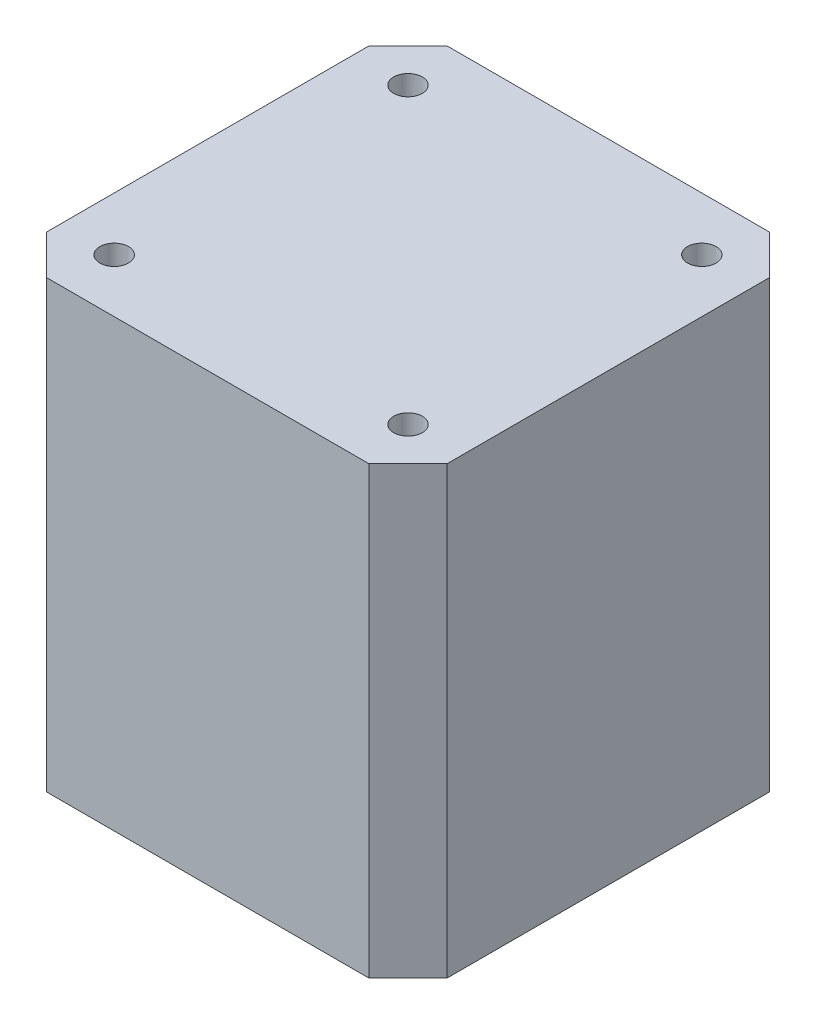
SolidWorks part; units mm, degrees
ref_plane "Front Plane" through (0, 0, 0) normal (0, 0, 1) x (1, 0, 0)
ref_plane "Top Plane" through (0, 0, 0) normal (0, 1, 0) x (1, 0, 0)
ref_plane "Right Plane" through (0, 0, 0) normal (1, 0, 0) x (0, 0, -1)
sketch "Sketch1" plane through (0, 0, 0) normal (0, 1, 0) x (1, 0, 0)
  line L0 (-17.01, 21.15) -> (-21.15, 17.01)
  line L1 (-17.01, -21.15) -> (17.01, -21.15)
  line L2 (-21.15, -17.01) -> (-21.15, 17.01)
  line L3 (-17.01, 21.15) -> (17.01, 21.15)
  line L4 (21.15, -17.01) -> (21.15, 17.01)
  line L5 (-21.15, -21.15) -> (21.15, 21.15) construction
  line L6 (-21.15, 21.15) -> (21.15, -21.15) construction
  line L7 (-21.15, 21.15) -> (-17.01, 21.15) construction
  line L8 (-21.15, 21.15) -> (-21.15, 17.01) construction
  line L9 (-21.15, 17.01) -> (-17.01, 17.01) construction
  line L10 (-17.01, 21.15) -> (-17.01, 17.01) construction
  line L11 (-21.15, 21.15) -> (-17.01, 17.01) construction
  line L12 (-21.15, 17.01) -> (-17.01, 21.15) construction
  line L13 (-17.01, 21.15) -> (-21.15, 17.01) construction
  line L14 (-21.15, -21.15) -> (-17.01, -21.15) construction
  line L15 (-21.15, -21.15) -> (-21.15, -17.01) construction
  line L16 (-21.15, -17.01) -> (-17.01, -17.01) construction
  line L17 (-17.01, -21.15) -> (-17.01, -17.01) construction
  line L18 (-21.15, -21.15) -> (-17.01, -17.01) construction
  line L19 (-21.15, -17.01) -> (-17.01, -21.15) construction
  line L20 (-17.01, 21.15) -> (-17.01, 17.01) construction
  line L21 (-21.15, 17.01) -> (-17.01, 17.01) construction
  line L22 (21.15, 17.01) -> (17.01, 21.15) construction
  line L23 (21.15, 17.01) -> (17.01, 17.01) construction
  line L24 (17.01, 21.15) -> (17.01, 17.01) construction
  line L25 (17.01, -21.15) -> (21.15, -17.01) construction
  line L26 (17.01, -21.15) -> (17.01, -17.01) construction
  line L27 (21.15, -17.01) -> (17.01, -17.01) construction
  line L28 (-21.15, -17.01) -> (-17.01, -21.15)
  line L29 (21.15, -17.01) -> (17.01, -21.15)
  line L30 (17.01, 21.15) -> (21.15, 17.01)
  circle A0 centre (15.5, 15.5) radius 1.51
  circle A1 centre (15.5, -15.5) radius 1.51
  circle A2 centre (-15.5, -15.5) radius 1.51
  circle A3 centre (-15.5, 15.5) radius 1.51
  point P1 (0, 0)
  point P8 (15.5, 15.5)
  point P19 (0, 0)
  point P22 (-19.08, 19.08)
  point P23 (-19.08, -19.08)
  point P24 (0, 0)
  point P36 (0, 0)
  dimension "D2" = 3.02
  dimension "D1" = 42.3
  dimension "D3" = 4
  dimension "D4" = 4
extrude "Boss-Extrude1" add sketch "Sketch1" along normal blind 47
sketch "Sketch2" plane through (0, 0, 0) normal (0, 1, 0) x (1, 0, 0)
  circle A0 centre (15.5, -15.5) radius 1.51
  circle A1 centre (-15.5, -15.5) radius 1.51
  circle A2 centre (-15.5, 15.5) radius 1.51
  circle A3 centre (15.5, 15.5) radius 1.51
  point P0 (15.5, -15.5)
  point P12 (0, 0)
  dimension "D1" = 3.02
  dimension "D2" = 4
sketch "Sketch4" plane through (0, 0, 0) normal (0, 1, 0) x (1, 0, 0)
  circle A0 centre (0, 0) radius 2.475
  dimension "D1" = 4.95
extrude "Boss-Extrude2" add sketch "Sketch4" against normal blind 10
fillet "Fillet1" radius 0.3 1 edges at (0, -10, 2.475)
